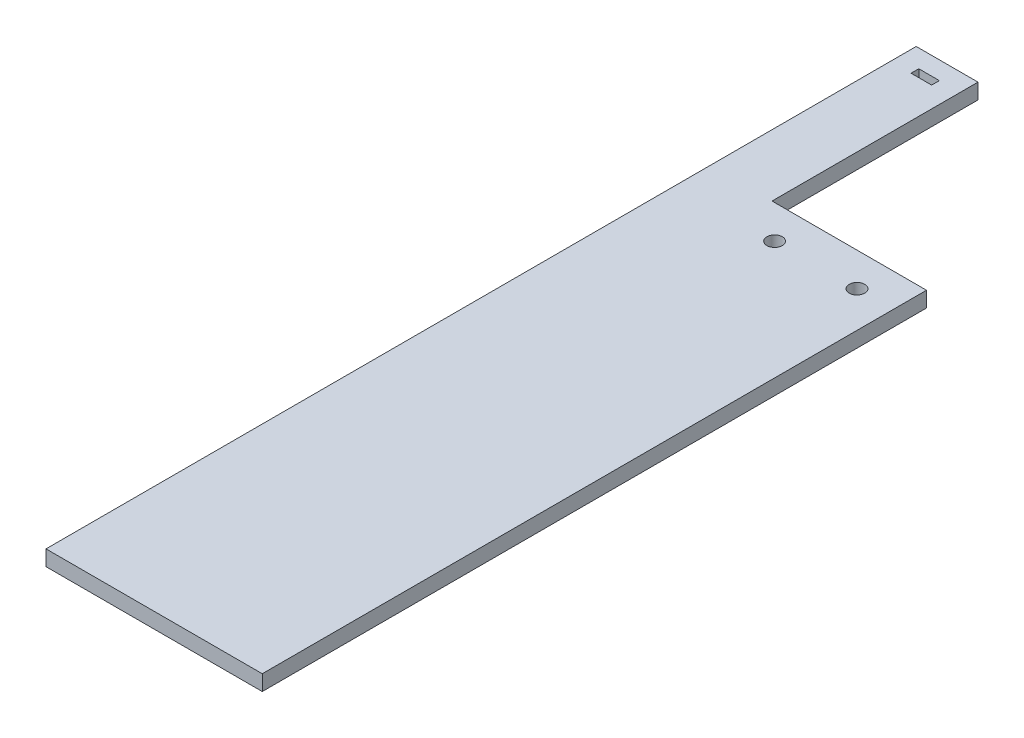
SolidWorks part; units mm, degrees
ref_plane "Front Plane" through (0, 0, 0) normal (0, 0, 1) x (1, 0, 0)
ref_plane "Top Plane" through (0, 0, 0) normal (0, 1, 0) x (1, 0, 0)
ref_plane "Right Plane" through (0, 0, 0) normal (1, 0, 0) x (0, 0, -1)
sketch "Sketch1" plane through (0, 0, 0) normal (0, 1, 0) x (1, 0, 0)
  line L0 (0, 129) -> (0, 169)
  line L1 (0, 0) -> (42, 0)
  line L2 (0, 0) -> (0, 129)
  line L4 (42, 0) -> (42, 129)
  line L5 (0, 169) -> (12, 169)
  line L7 (12, 169) -> (12, 129)
  line L8 (4, 165.5) -> (8, 165.5)
  line L9 (4, 165.5) -> (4, 164)
  line L10 (4, 164) -> (8, 164)
  line L11 (8, 165.5) -> (8, 164)
  line L12 (12, 129) -> (42, 129)
  line L13 (19, 122.5) -> (35, 122.5) construction
  circle A1 centre (19, 122.5) radius 1.5
  circle A2 centre (35, 122.5) radius 1.5
  point P16 (27, 122.5)
  point P17 (27, 129)
  dimension "D5" = 35
  dimension "D9" = 3
  dimension "D10" = 3
  dimension "D1" = 42
  dimension "D2" = 129
  dimension "D3" = 40
  dimension "D4" = 12
  dimension "D6" = 1.5
  dimension "D7" = 4
  dimension "D8" = 4
  dimension "D11" = 16
  dimension "D12" = 6.5
extrude "Boss-Extrude1" add sketch "Sketch1" along normal blind 3
